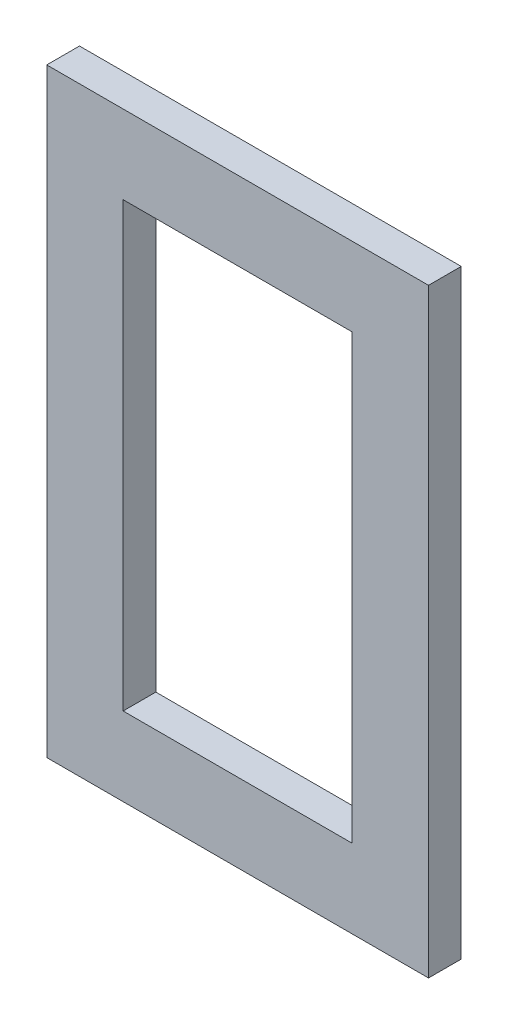
SolidWorks part; units mm, degrees
ref_plane "Front Plane" through (0, 0, 0) normal (0, 0, 1) x (1, 0, 0)
ref_plane "Top Plane" through (0, 0, 0) normal (0, 1, 0) x (1, 0, 0)
ref_plane "Right Plane" through (0, 0, 0) normal (1, 0, 0) x (0, 0, -1)
sketch "Sketch1" plane through (0, 0, 0) normal (0, 0, 1) x (1, 0, 0)
  line L1 (17.5, -27.5) -> (-17.5, -27.5)
  line L2 (17.5, -27.5) -> (17.5, 27.5)
  line L3 (17.5, 27.5) -> (-17.5, 27.5)
  line L4 (-17.5, -27.5) -> (-17.5, 27.5)
  line L5 (17.5, -27.5) -> (-17.5, 27.5) construction
  line L6 (17.5, 27.5) -> (-17.5, -27.5) construction
  point P0 (0, 0)
  dimension "D1" = 35
  dimension "D2" = 55
extrude "Boss-Extrude1" add sketch "Sketch1" along normal blind 3
sketch "Sketch2" plane through (0, 0, 3) normal (0, 0, 1) x (1, 0, 0)
  line L1 (10.5, -20.3) -> (-10.5, -20.3)
  line L2 (10.5, -20.3) -> (10.5, 20.3)
  line L3 (10.5, 20.3) -> (-10.5, 20.3)
  line L4 (-10.5, -20.3) -> (-10.5, 20.3)
  line L5 (10.5, -20.3) -> (-10.5, 20.3) construction
  line L6 (10.5, 20.3) -> (-10.5, -20.3) construction
  point P0 (0, 0)
  dimension "D1" = 21
  dimension "D2" = 40.6
extrude "Cut-Extrude1" cut sketch "Sketch2" against normal blind 3
